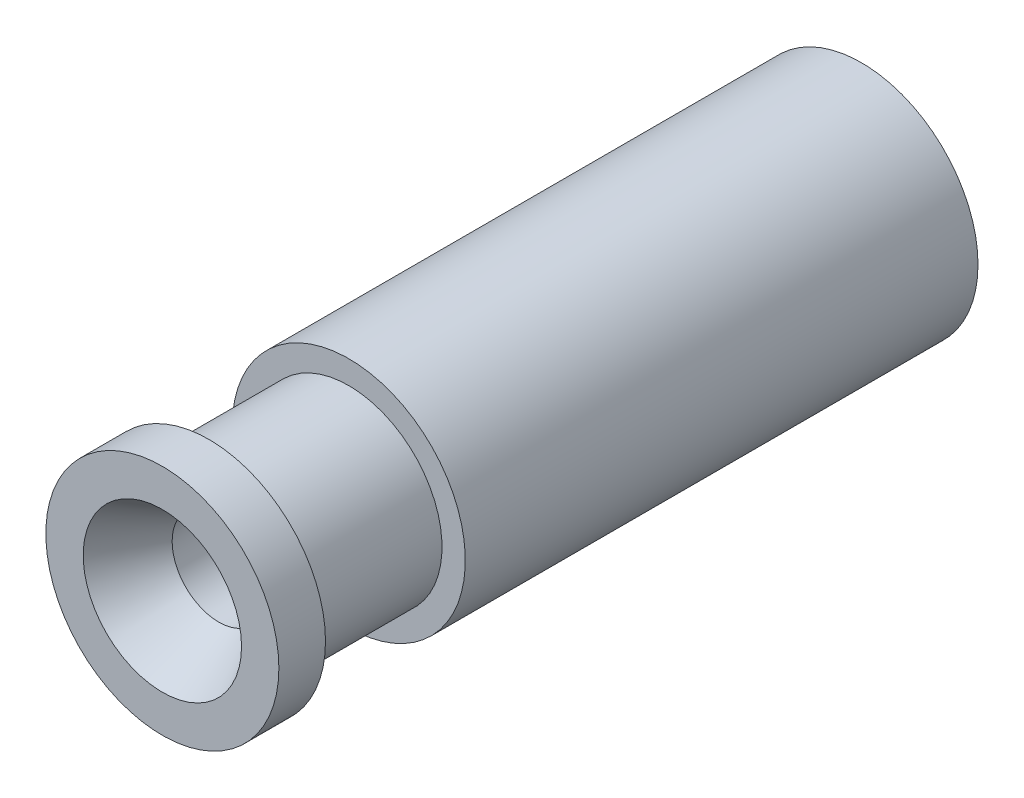
SolidWorks part; units mm, degrees
ref_plane "Front Plane" through (0, 0, 0) normal (0, 0, 1) x (1, 0, 0)
ref_plane "Top Plane" through (0, 0, 0) normal (0, 1, 0) x (1, 0, 0)
ref_plane "Right Plane" through (0, 0, 0) normal (1, 0, 0) x (0, 0, -1)
sketch "Sketch1" plane through (0, 0, 0) normal (0, 0, 1) x (1, 0, 0)
  circle A0 centre (0, 0) radius 2.5
  dimension "D1" = 5
extrude "Boss-Extrude1" add sketch "Sketch1" along normal blind 15
sketch "Sketch2" plane through (0, 0, 0) normal (0, 0, -1) x (-1, 0, 0)
  circle A0 centre (0, 0) radius 1
  dimension "D1" = 2
extrude "Cut-Extrude1" cut sketch "Sketch2" against normal through all
hole_wizard "Tap Drill for M4x0.7 Tap1" positions "Sketch4" profile "Sketch3" hole size "M4x0.7" standard "ANSI Metric"
sketch "Sketch4" plane through (0, 0, 0) normal (0, 0, -1) x (-1, 0, 0)
  point P0 (0, 0)
sketch "Sketch3" plane through (0, 0, 0) normal (1, 0, 0) x (0, 1, 0)
  line L0 (0, 0) -> (0, 9.9914)
  line L1 (0, 9.9914) -> (1.65, 9)
  line L2 (1.65, 9) -> (1.65, 0)
  line L5 (1.65, 0) -> (0, 0)
  line L10 (0, 9.9914) -> (-1.65, 9) construction
  line L11 (0, -6.35) -> (0, 107.95) construction
  dimension "Hole Dia." = 3.3
  dimension "Hole Depth" = 9
  dimension "Drill Angle" = 118
cosmetic thread "Cosmetic Thread1" parameters "D1"=8, "D2"=4
sketch "Sketch5" plane through (0, 0, 0) normal (1, 0, 0) x (0, 0, -1)
  line L0 (0, 0) -> (-16.1108, 0) construction
  line L1 (-14, 3.7938) -> (-11, 3.7938)
  line L2 (-14, 3.7938) -> (-14, 2)
  line L3 (-14, 2) -> (-11, 2)
  line L4 (-11, 3.7938) -> (-11, 2)
  dimension "D1" = 11
  dimension "D2" = 14
  dimension "D3" = 4
revolve "Cut-Revolve1" cut sketch "Sketch5" angle 360 mid plane about L0
chamfer "Chamfer1" distance 0.5 angle 60 1 edges at (-1.65, 0, 0)
chamfer "Chamfer2" distance 1.21 angle 30 1 edges at (-1, 0, 15)
